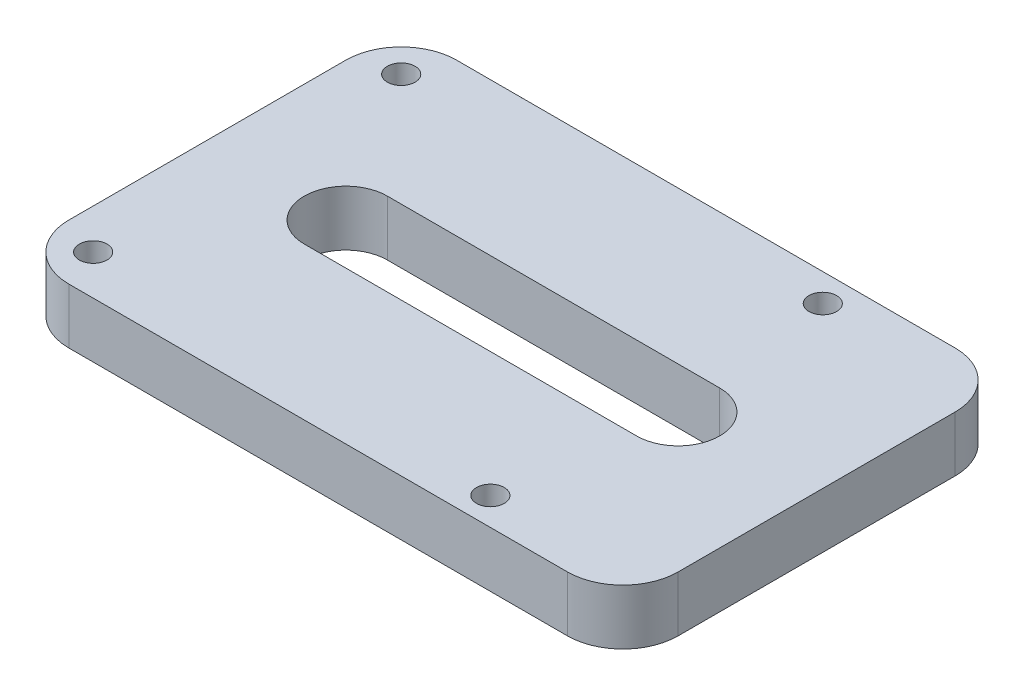
SolidWorks part; units mm, degrees
ref_plane "Front Plane" through (0, 0, 0) normal (0, 0, 1) x (1, 0, 0)
ref_plane "Top Plane" through (0, 0, 0) normal (0, 1, 0) x (1, 0, 0)
ref_plane "Right Plane" through (0, 0, 0) normal (1, 0, 0) x (0, 0, -1)
sketch "Sketch1" plane through (0, 0, 0) normal (0, 1, 0) x (1, 0, 0)
  line L0 (0, 0) -> (-47.8, 0) construction
  line L1 (-45, -35) -> (45, -35)
  line L2 (-55, -25) -> (-55, 25)
  line L3 (-45, 35) -> (45, 35)
  line L4 (55, -25) -> (55, 25)
  line L5 (-55, -35) -> (55, 35) construction
  line L6 (-55, 35) -> (55, -35) construction
  line L7 (-47.8, 0) -> (-47.8, 27.8) construction
  line L9 (-30, 0) -> (30, 0) construction
  line L10 (-30, 7.5) -> (30, 7.5)
  line L11 (-30, -7.5) -> (30, -7.5)
  line L12 (0, 0) -> (0, 30) construction
  line L13 (0, 30) -> (26.1, 30) construction
  arc A0 (-45, -35) -> (-55, -25) centre (-45, -25) cw
  arc A1 (45, -35) -> (55, -25) centre (45, -25) ccw
  arc A2 (45, 35) -> (55, 25) centre (45, 25) cw
  arc A3 (-55, 25) -> (-45, 35) centre (-45, 25) cw
  circle A4 centre (-47.8, 27.8) radius 2.5
  circle A5 centre (-47.8, -27.8) radius 2.5
  arc A8 (-30, 7.5) -> (-30, -7.5) centre (-30, 0) ccw
  arc A9 (30, -7.5) -> (30, 7.5) centre (30, 0) ccw
  circle A10 centre (26.1, 30) radius 2.5
  circle A11 centre (26.1, -30) radius 2.5
  point P0 (0, 0)
  point P32 (0, 0)
  dimension "D3" = 10
  dimension "D6" = 25
  dimension "D7" = 25
  dimension "D1" = 110
  dimension "D2" = 70
  dimension "D4" = 47.8
  dimension "D5" = 27.8
  dimension "D8" = 26.1
  dimension "D9" = 30
extrude "Boss-Extrude1" add sketch "Sketch1" along normal blind 10
